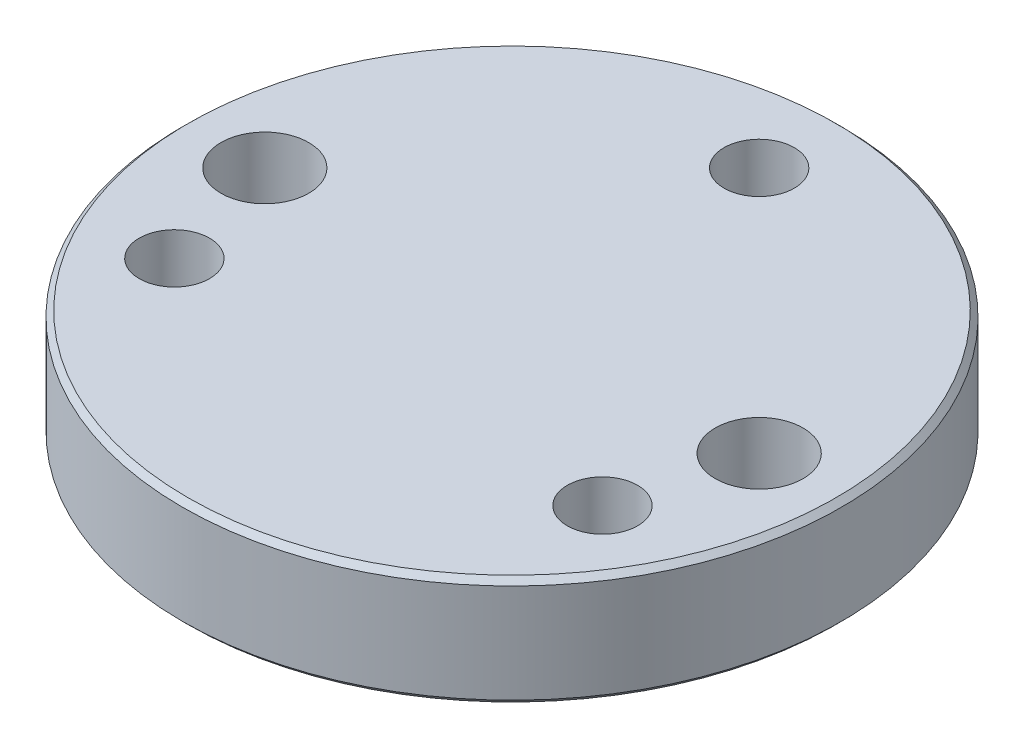
SolidWorks part; units mm, degrees
material "K110"
ref_plane "Front Plane" through (0, 0, 0) normal (0, 0, 1) x (1, 0, 0)
ref_plane "Top Plane" through (0, 0, 0) normal (0, 1, 0) x (1, 0, 0)
ref_plane "Right Plane" through (0, 0, 0) normal (1, 0, 0) x (0, 0, -1)
sketch "Sketch1" plane through (0, 0, 0) normal (0, 1, 0) x (1, 0, 0)
  circle A0 centre (0, 0) radius 30
  dimension "D1" = 60
extrude "Boss-Extrude1" add sketch "Sketch1" against normal blind 10
hole_wizard "Ø8.0mm Dowel Hole1" positions "Sketch6" profile "Sketch5" hole size "Ø8.0" standard "ISO" end condition through all
sketch "Sketch6" plane through (0, 0, 0) normal (0, 1, 0) x (1, 0, 0)
  point P0 (-22.5, 0)
  point P3 (22.5, 0)
sketch "Sketch5" plane through (-22.5, 0, 0) normal (1, 0, 0) x (0, 0, 1)
  line L0 (0, 0) -> (0, 10)
  line L1 (0, 10) -> (4, 10)
  line L2 (4, 10) -> (4, 0)
  line L5 (4, 0) -> (0, 0)
  line L11 (0, -6.35) -> (0, 107.95) construction
  dimension "Thru Hole Dia." = 8
  dimension "Thru Hole Depth" = 10
hole_wizard "M6 Clearance Hole1" positions "Sketch10" profile "Sketch8" hole size "M6" standard "ISO" end condition through all
sketch "Sketch10" plane through (0, 0, 0) normal (0, 1, 0) x (1, 0, 0)
  circle A0 centre (0, 0) radius 22.5 construction
  point P0 (19.4856, -11.25)
  point P3 (-19.4856, -11.25)
  point P6 (0, 22.5)
  dimension "D1" = 45
sketch "Sketch8" plane through (19.4856, 0, 11.25) normal (1, 0, 0) x (0, 0, 1)
  line L0 (0, 0) -> (0, 10)
  line L1 (0, 10) -> (3.2, 10)
  line L2 (3.2, 10) -> (3.2, 0)
  line L5 (3.2, 0) -> (0, 0)
  line L11 (0, -6.35) -> (0, 107.95) construction
  dimension "Thru Hole Dia." = 6.4
  dimension "Thru Hole Depth" = 10
chamfer "Chamfer1" distance 0.5 angle 45 2 edges at (0, -10, 30) (0, 0, 30)
